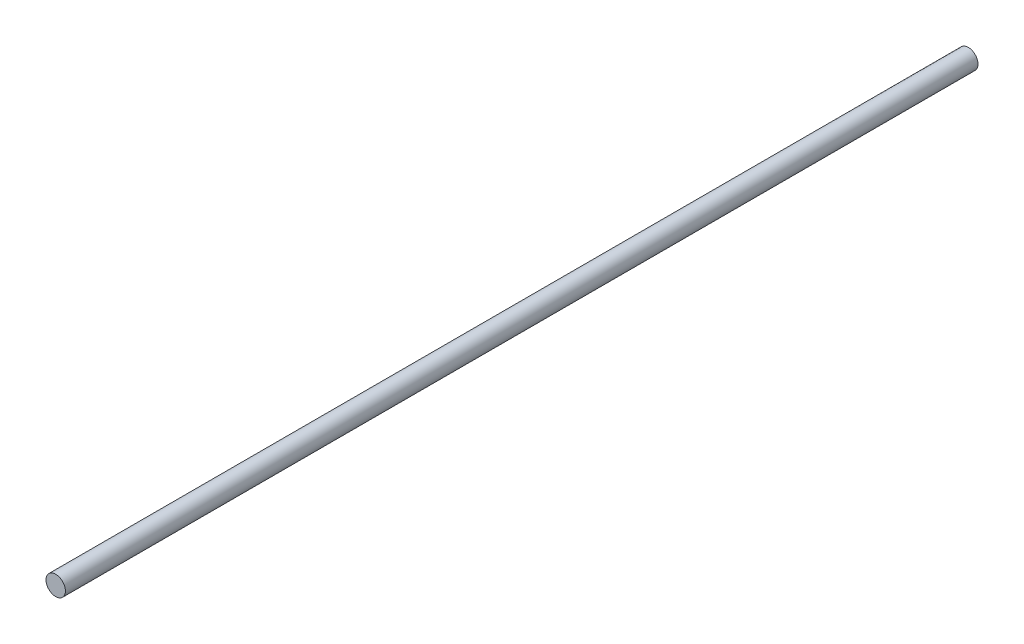
SolidWorks part; units mm, degrees
ref_plane "Piano frontale" through (0, 0, 0) normal (0, 0, 1) x (1, 0, 0)
ref_plane "Piano superiore" through (0, 0, 0) normal (0, 1, 0) x (1, 0, 0)
ref_plane "Piano destro" through (0, 0, 0) normal (1, 0, 0) x (0, 0, -1)
sketch "Schizzo1" plane through (0, 0, 0) normal (0, 0, 1) x (1, 0, 0)
  circle A0 centre (0, 0) radius 4
  dimension "D1" = 8
extrude "Estrusione-Estrusione2" add sketch "Schizzo1" against normal blind 375.7 contours A0
cosmetic thread "Filettatura cosmetica2" parameters "D1"=275.7, "D2"=6.619
